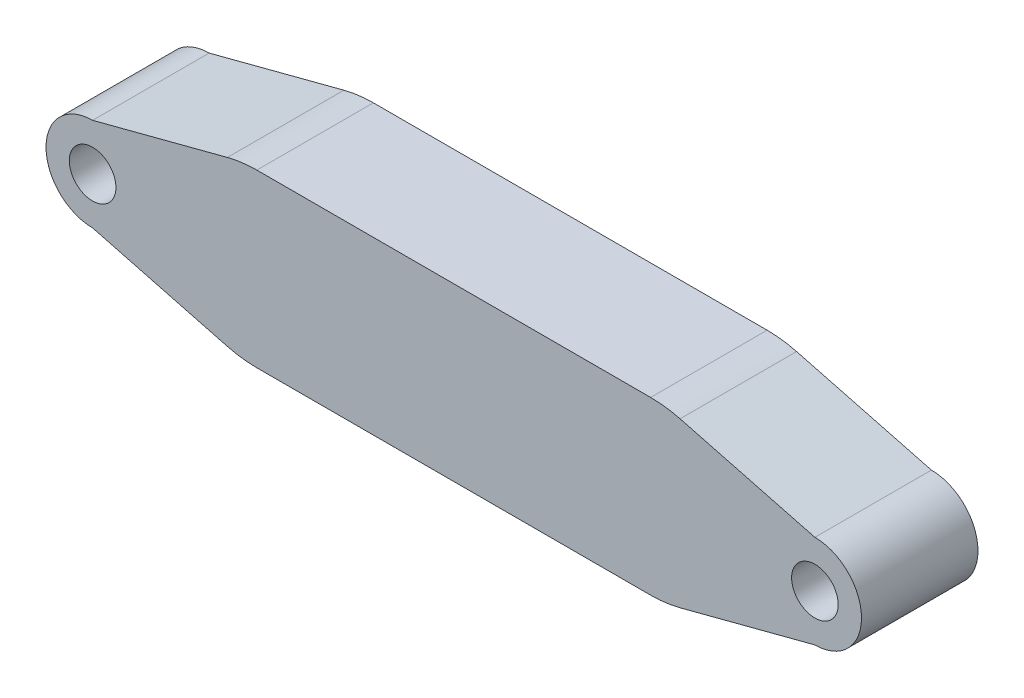
SolidWorks part; units mm, degrees
ref_plane "Alzado" through (0, 0, 0) normal (0, 0, 1) x (1, 0, 0)
ref_plane "Planta" through (0, 0, 0) normal (0, 1, 0) x (1, 0, 0)
ref_plane "Vista lateral" through (0, 0, 0) normal (1, 0, 0) x (0, 0, -1)
sketch "Croquis1" plane through (0, 0, 0) normal (0, 0, 1) x (1, 0, 0)
  line L0 (0, 0) -> (62, 0) construction
  line L1 (12.815, 7.35) -> (49.185, 7.35)
  line L2 (0, 4) -> (12.815, 7.35)
  line L3 (49.185, 7.35) -> (62, 4)
  line L4 (49.185, -7.35) -> (62, -4)
  line L5 (12.815, -7.35) -> (49.185, -7.35)
  line L6 (0, -4) -> (12.815, -7.35)
  circle A0 centre (0, 0) radius 2
  arc A1 (0, 4) -> (0, -4) centre (0, 0) ccw
  arc A2 (62, -4) -> (62, 4) centre (62, 0) ccw
  circle A3 centre (62, 0) radius 2
  point P10 (31, 7.35)
  point P11 (31, 0)
  dimension "D1" = 4
  dimension "D2" = 8
  dimension "D3" = 62
  dimension "D4" = 7.35
  dimension "D5" = 36.37
extrude "Saliente-Extruir1" add sketch "Croquis1" along normal blind 10
fillet "Redondeo2" radius 10 4 edges at (12.815, -7.35, 5) (12.815, 7.35, 5) (49.185, 7.35, 5) (49.185, -7.35, 5)
